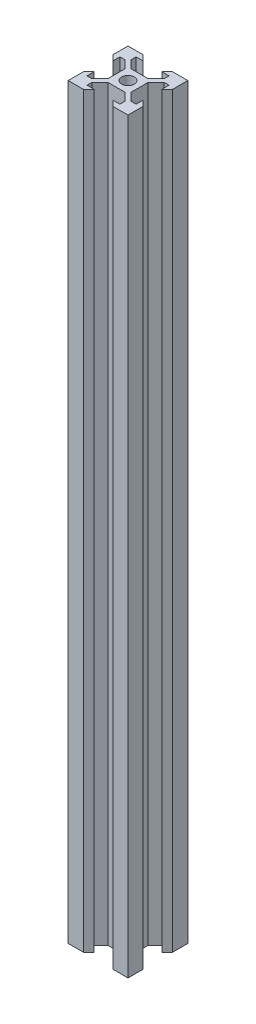
SolidWorks part; units mm, degrees
ref_plane "Front Plane" through (0, 0, 0) normal (0, 0, 1) x (1, 0, 0)
ref_plane "Top Plane" through (0, 0, 0) normal (0, 1, 0) x (1, 0, 0)
ref_plane "Right Plane" through (0, 0, 0) normal (1, 0, 0) x (0, 0, -1)
sketch "Sketch1" plane through (0, 0, 0) normal (0, 1, 0) x (1, 0, 0)
  line L0 (3.9007, 2.84) -> (2.84, 3.9007) construction
  line L1 (-10, -10) -> (10, -10) construction
  line L2 (-10, -10) -> (-10, 10) construction
  line L3 (-10, 10) -> (10, 10) construction
  line L4 (10, -10) -> (10, 10) construction
  line L5 (-10, -10) -> (10, 10) construction
  line L6 (-10, 10) -> (10, -10) construction
  line L7 (-2.84, -2.84) -> (2.84, -2.84) construction
  line L8 (-2.84, -2.84) -> (-2.84, 2.84) construction
  line L9 (-2.84, 2.84) -> (2.84, 2.84) construction
  line L10 (2.84, -2.84) -> (2.84, 2.84) construction
  line L11 (-2.84, -2.84) -> (2.84, 2.84) construction
  line L12 (-2.84, 2.84) -> (2.84, -2.84) construction
  line L13 (2.84, -3.9007) -> (3.9007, -2.84) construction
  line L14 (-3.9007, -2.84) -> (-2.84, -3.9007) construction
  line L15 (-2.84, 3.9007) -> (-3.9007, 2.84) construction
  line L16 (-3.1, 10) -> (3.1, 10) construction
  line L17 (-3.1, 10) -> (-3.1, 8.2) construction
  line L18 (-3.1, 8.2) -> (-4.9, 10)
  line L19 (3.1, 8.2) -> (3.1, 10) construction
  line L20 (-3.1, 8.2) -> (-8.2, 8.2) construction
  line L21 (-2.84, 3.9007) -> (-7.1393, 8.2) construction
  line L22 (-5.4993, 8.2) -> (-5.4993, 6.56)
  line L23 (-4.9, 10) -> (-10, 10)
  line L24 (-3.9007, -3.9007) -> (3.9007, -3.9007) construction
  line L25 (-3.9007, -3.9007) -> (-3.9007, 3.9007) construction
  line L26 (-3.9007, 3.9007) -> (3.9007, 3.9007) construction
  line L27 (3.9007, -3.9007) -> (3.9007, 3.9007) construction
  line L28 (-3.9007, -3.9007) -> (3.9007, 3.9007) construction
  line L29 (-3.9007, 3.9007) -> (3.9007, -3.9007) construction
  line L30 (-5.4993, 6.56) -> (-2.84, 3.9007)
  line L31 (-2.84, 3.9007) -> (0, 3.9007)
  line L32 (-5.4993, 8.2) -> (-3.1, 8.2)
  line L33 (-3.9007, 2.84) -> (-3.9007, 0)
  line L34 (-6.56, 5.4993) -> (-3.9007, 2.84)
  line L35 (-8.2, 5.4993) -> (-6.56, 5.4993)
  line L36 (-8.2, 5.4993) -> (-8.2, 3.1)
  line L37 (-8.2, 3.1) -> (-10, 4.9)
  line L38 (-10, 4.9) -> (-10, 10)
  line L39 (2.84, 3.9007) -> (0, 3.9007)
  line L40 (5.4993, 6.56) -> (2.84, 3.9007)
  line L41 (5.4993, 8.2) -> (5.4993, 6.56)
  line L42 (5.4993, 8.2) -> (3.1, 8.2)
  line L43 (3.1, 8.2) -> (4.9, 10)
  line L44 (4.9, 10) -> (10, 10)
  line L45 (10, 4.9) -> (10, 10)
  line L46 (8.2, 3.1) -> (10, 4.9)
  line L47 (8.2, 5.4993) -> (8.2, 3.1)
  line L48 (8.2, 5.4993) -> (6.56, 5.4993)
  line L49 (6.56, 5.4993) -> (3.9007, 2.84)
  line L50 (3.9007, 2.84) -> (3.9007, 0)
  line L51 (3.9007, -2.84) -> (3.9007, 0)
  line L52 (6.56, -5.4993) -> (3.9007, -2.84)
  line L53 (8.2, -5.4993) -> (6.56, -5.4993)
  line L54 (8.2, -5.4993) -> (8.2, -3.1)
  line L55 (8.2, -3.1) -> (10, -4.9)
  line L56 (10, -4.9) -> (10, -10)
  line L57 (4.9, -10) -> (10, -10)
  line L58 (3.1, -8.2) -> (4.9, -10)
  line L59 (5.4993, -8.2) -> (3.1, -8.2)
  line L60 (5.4993, -8.2) -> (5.4993, -6.56)
  line L61 (5.4993, -6.56) -> (2.84, -3.9007)
  line L62 (2.84, -3.9007) -> (0, -3.9007)
  line L63 (-2.84, -3.9007) -> (0, -3.9007)
  line L64 (-5.4993, -6.56) -> (-2.84, -3.9007)
  line L65 (-5.4993, -8.2) -> (-5.4993, -6.56)
  line L66 (-5.4993, -8.2) -> (-3.1, -8.2)
  line L67 (-3.1, -8.2) -> (-4.9, -10)
  line L68 (-4.9, -10) -> (-10, -10)
  line L69 (-10, -4.9) -> (-10, -10)
  line L70 (-8.2, -3.1) -> (-10, -4.9)
  line L71 (-8.2, -5.4993) -> (-8.2, -3.1)
  line L72 (-8.2, -5.4993) -> (-6.56, -5.4993)
  line L73 (-6.56, -5.4993) -> (-3.9007, -2.84)
  line L74 (-3.9007, -2.84) -> (-3.9007, 0)
  circle A0 centre (0, 0) radius 2.1
  circle A1 centre (0, 0) radius 2.1
  circle A2 centre (0, 0) radius 2.1
  circle A3 centre (0, 0) radius 2.1
  point P0 (0, 0)
  point P15 (3.3703, 3.3703)
  point P27 (0, 0)
  point P28 (0, 10)
  point P87 (0, 0)
  dimension "D2" = 4.2
  dimension "D1" = 20
  dimension "D3" = 5.68
  dimension "D4" = 1.5
  dimension "D6" = 6.2
  dimension "D7" = 1.8
  dimension "D8" = 45
  dimension "D9" = 1.64
  dimension "D10" = 4
  dimension "D11" = 90
  dimension "D12" = 1.64
  dimension "D13" = 20
  dimension "D14" = 1.5
  dimension "D15" = 5.68
  dimension "D16" = 6.2
  dimension "D17" = 1.8
  dimension "D5" = 4
extrude "Boss-Extrude1" add sketch "Sketch1" along normal blind 250 contours L74 L73 L72 L71 L70 L69 L68 L67 L66 L65 L64 L63 L62 L61 L60 L59 L58 L57 L56 L55 L54 L53 L52 L51 L50 L49 L48 L47 L46 L45 L44 L43 L42 L41 L40 L39 L31 L30 L22 L32 L18 L23 L38 L37 L36 L35 L34 L33 A0
